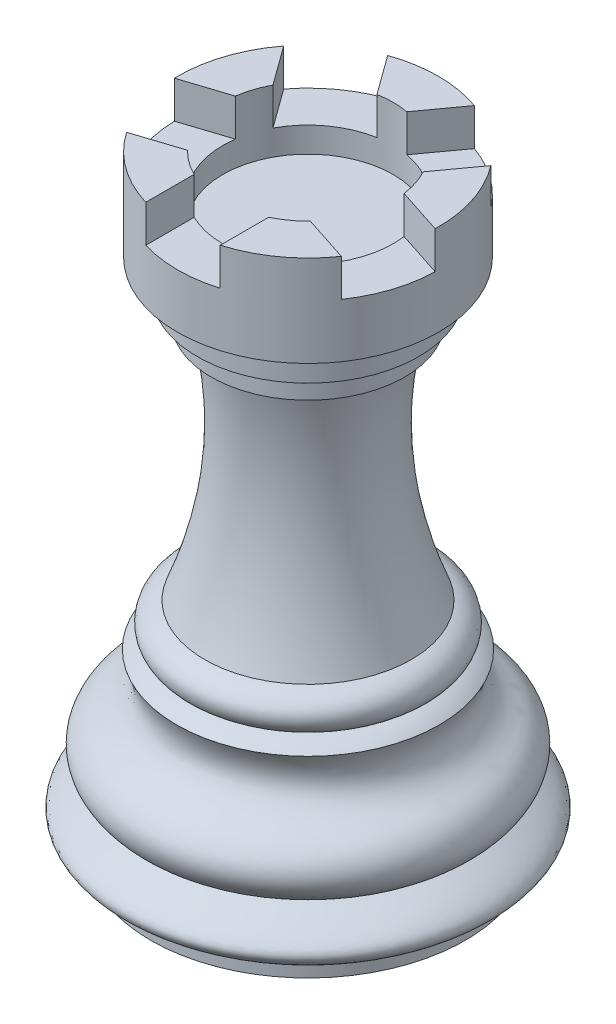
SolidWorks part; units mm, degrees
ref_plane "Front Plane" through (0, 0, 0) normal (0, 0, 1) x (1, 0, 0)
ref_plane "Top Plane" through (0, 0, 0) normal (0, 1, 0) x (1, 0, 0)
ref_plane "Right Plane" through (0, 0, 0) normal (1, 0, 0) x (0, 0, -1)
sketch "Sketch1" plane through (0, 0, 0) normal (0, 0, 1) x (1, 0, 0)
  line L0 (-75.1451, 533.1501) -> (-115.0422, 533.1501)
  line L1 (0, 0) -> (0, 478.0632)
  line L2 (0, 0) -> (-138.7506, 0)
  line L3 (-138.7506, 0) -> (-138.7506, 10.7834)
  line L4 (-115.0422, 533.1501) -> (-115.0422, 452.6055)
  line L5 (-115.0422, 452.6055) -> (-104.7641, 452.6055)
  line L6 (-97.5169, 425.1921) -> (-97.5169, 440.6318)
  line L7 (-75.1451, 397.7787) -> (-75.1451, 403.4505)
  line L8 (-75.1451, 403.4505) -> (-85.2281, 403.4505)
  line L9 (-85.2281, 403.4505) -> (-85.2281, 416.3694)
  line L10 (-75.1451, 397.7787) -> (-71.9505, 397.7787)
  line L12 (-75.1451, 533.1501) -> (-75.1451, 478.0632)
  line L13 (-75.1451, 478.0632) -> (0, 478.0632)
  spline S0 degree 2 poles (-71.9505, 397.7787) (-50.3503, 296.0086) (-91.0824, 190.5858) knots 0 0 0 1 1 1
  spline S1 degree 3 poles (-91.0824, 190.5858) (-112.6606, 184.5365) (-111.403, 167.6509) (-100.6895, 160.7685) knots 0 0 0 0 1 1 1 1
  spline S2 degree 2 poles (-100.6895, 160.7685) (-108.8242, 158.3899) (-115.7985, 153.0845) knots 0 0 0 1 1 1
  spline S3 degree 3 poles (-115.7985, 153.0845) (-107.7223, 137.5865) (-104.646, 118.842) (-145.3045, 100.0228) (-157.9545, 76.9788) (-138.696, 57.7752) (-130.8898, 55.7806) knots 0 0 0 0 0.533073 0.606266 0.825963 1 1 1 1
  spline S4 degree 3 poles (-130.8898, 55.7806) (-177.2819, 34.3787) (-168.9434, 29.4802) (-138.7506, 10.7834) knots 0 0 0 0 1 1 1 1
  spline S5 degree 2 poles (-85.2281, 416.3694) (-84.9368, 423.9278) (-97.5169, 425.1921) knots 0 0 0 1 1 1
  spline S6 degree 3 poles (-97.5169, 440.6318) (-98.1289, 451.3788) (-101.6852, 452.0807) (-104.7641, 452.6055) knots 0 0 0 0 1 1 1 1
  point P11 (-91.0824, 190.5858)
  point P14 (-100.6895, 160.7685)
  point P15 (-115.7985, 153.0845)
  point P16 (-130.8898, 55.7806)
  dimension "D1" = 71.9505
  dimension "D2" = 75.1451
  dimension "D3" = 85.2281
  dimension "D4" = 91.0824
  dimension "D5" = 97.5169
  dimension "D6" = 100.6895
  dimension "D7" = 104.7641
  dimension "D8" = 111.3514
  dimension "D9" = 115.0422
  dimension "D10" = 115.7985
  dimension "D11" = 130.8898
  dimension "D12" = 133.9639
  dimension "D13" = 138.7506
  dimension "D14" = 148.2014
  dimension "D15" = 10.7834
  dimension "D16" = 55.7806
  dimension "D17" = 70.7857
  dimension "D18" = 105.1232
  dimension "D19" = 142.392
  dimension "D20" = 153.0845
  dimension "D21" = 160.7685
  dimension "D22" = 190.5858
  dimension "D23" = 397.7787
  dimension "D24" = 403.4505
  dimension "D25" = 416.3694
  dimension "D26" = 425.1921
  dimension "D27" = 440.6318
  dimension "D28" = 452.6055
  dimension "D29" = 478.0632
  dimension "D30" = 533.1501
revolve "Revolve3" add sketch "Sketch1" angle 360 about L1
sketch "Sketch2" plane through (0, 0, 0) normal (0, 0, 1) x (1, 0, 0)
  line L0 (0, 547.506) -> (0, 492.7444) construction
  line L1 (75.1451, 533.1501) -> (-75.1451, 533.1501) construction
  line L2 (32.8323, 500.2825) -> (-32.8323, 500.2825)
  line L3 (-32.8323, 500.2825) -> (-32.8323, 533.1501)
  line L4 (-32.8323, 533.1501) -> (32.8323, 533.1501)
  line L5 (32.8323, 500.2825) -> (32.8323, 533.1501)
  point P8 (0, 500.2825)
  point P12 (0, 533.1501)
extrude "Cut-Extrude1" cut sketch "Sketch2" along normal up to next
pattern_circular "CirPattern1" count 5 over 360 about axis through (0, 0, 0) along (0, 1, 0) of "Cut-Extrude1"
scale "Scale1" scale about origin uniform scaling yes scale factor 0.5
